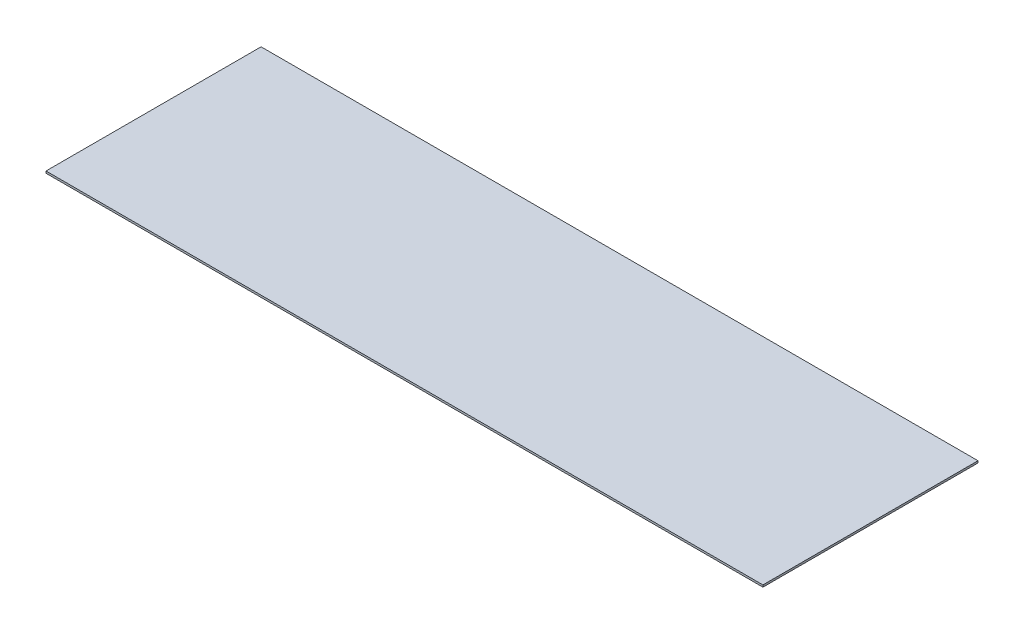
SolidWorks part; units mm, degrees
ref_plane "Front Plane" through (0, 0, 0) normal (0, 0, 1) x (1, 0, 0)
ref_plane "Top Plane" through (0, 0, 0) normal (0, 1, 0) x (1, 0, 0)
ref_plane "Right Plane" through (0, 0, 0) normal (1, 0, 0) x (0, 0, -1)
sketch "Sketch1" plane through (0, 0, 0) normal (0, 1, 0) x (1, 0, 0)
  line L1 (-900, -270) -> (900, -270)
  line L2 (-900, -270) -> (-900, 270)
  line L3 (-900, 270) -> (900, 270)
  line L4 (900, -270) -> (900, 270)
  line L5 (-900, -270) -> (900, 270) construction
  line L6 (-900, 270) -> (900, -270) construction
  point P0 (0, 0)
  dimension "D1" = 1800
  dimension "D2" = 540
extrude "Boss-Extrude1" add sketch "Sketch1" along normal blind 5
